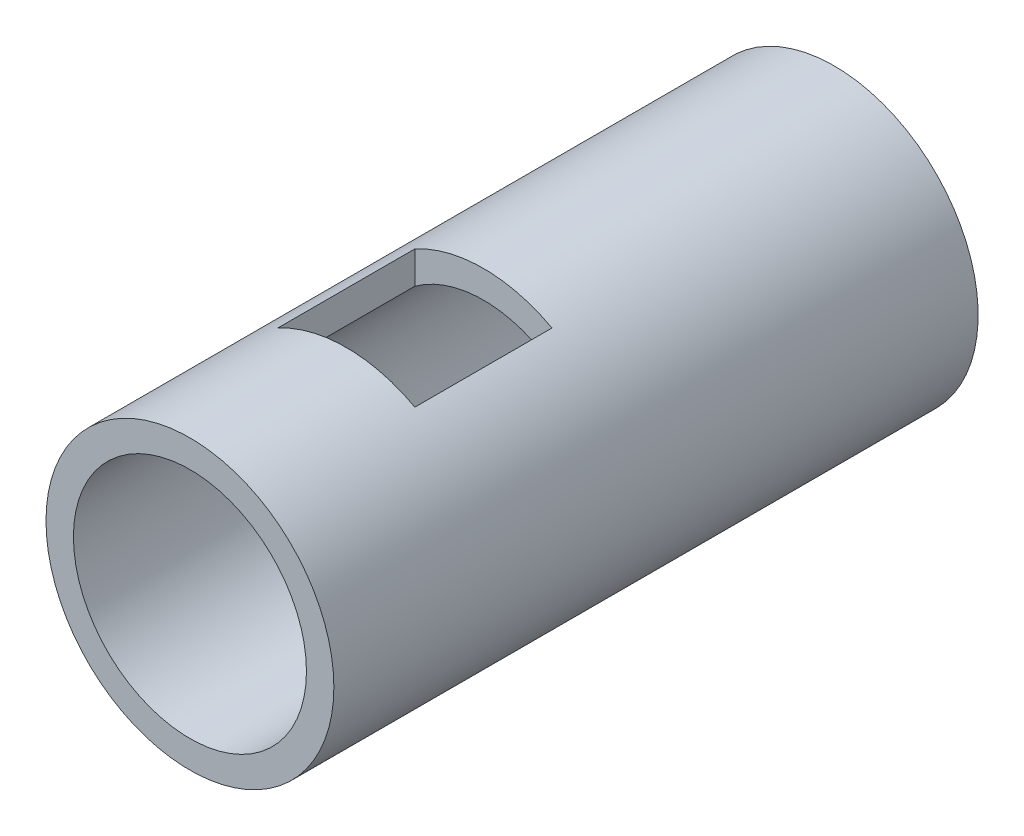
SolidWorks part; units mm, degrees
ref_plane "Front Plane" through (0, 0, 0) normal (0, 0, 1) x (1, 0, 0)
ref_plane "Top Plane" through (0, 0, 0) normal (0, 1, 0) x (1, 0, 0)
ref_plane "Right Plane" through (0, 0, 0) normal (1, 0, 0) x (0, 0, -1)
sketch "Sketch1" plane through (0, 0, 0) normal (0, 0, 1) x (1, 0, 0)
  circle A0 centre (0, 0) radius 8.5
  circle A1 centre (0, 0) radius 10.5
  dimension "D1" = 17
  dimension "D2" = 2
extrude "Boss-Extrude1" add sketch "Sketch1" along normal blind 45
sketch "Sketch2" plane through (0, 0, 0) normal (0, 1, 0) x (1, 0, 0)
  line L0 (0, 0) -> (0, -39.9607) construction
  line L2 (-5, -23.5892) -> (5, -23.5892)
  line L3 (-5, -23.5892) -> (-5, -33.5892)
  line L4 (-5, -33.5892) -> (5, -33.5892)
  line L5 (5, -23.5892) -> (5, -33.5892)
  line L6 (-5, -23.5892) -> (5, -33.5892) construction
  line L7 (-5, -33.5892) -> (5, -23.5892) construction
  point P3 (0, -28.5892)
  dimension "D1" = 10
  dimension "D2" = 10
extrude "Cut-Extrude1" cut sketch "Sketch2" along normal blind 40
sketch "Sketch6" plane through (0, 0, 0) normal (0, 0, -1) x (-1, 0, 0)
  line L0 (-8.5, 0) -> (8.5, 0)
  circle A0 centre (0, 0) radius 10.5 construction
  circle A1 centre (0, 0) radius 10.5
  circle A2 centre (0, 0) radius 8.5 construction
  circle A3 centre (0, 0) radius 8.5
  circle M3 centre (0, 0) radius 10.5
  circle M4 centre (0, 0) radius 8.5
extrude "Boss-Extrude4" add sketch "Sketch6" along normal blind 2 contours L0 M4 | M3 M4
